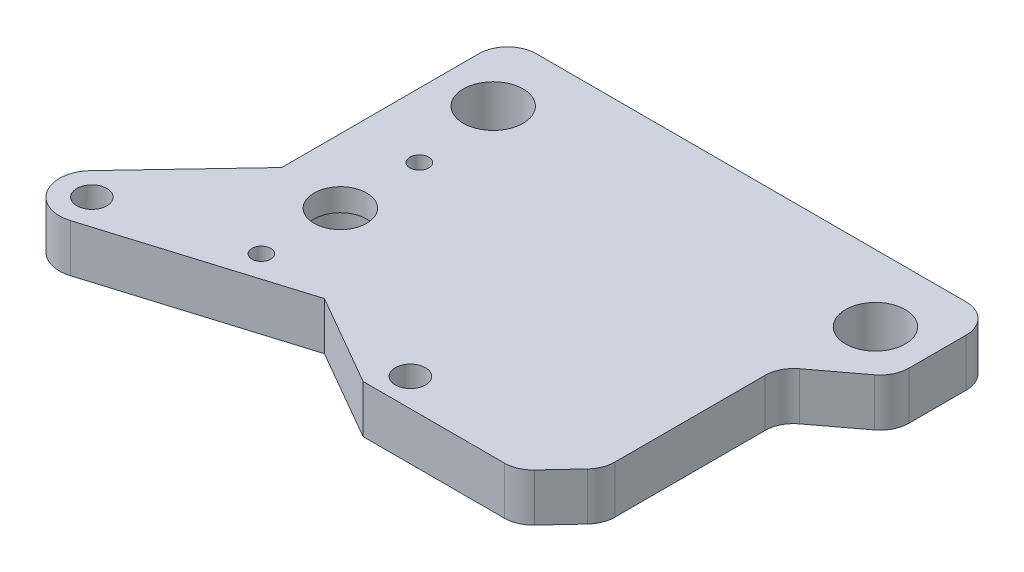
SolidWorks part; units mm, degrees
other "Markup1"
sketch "Sketch6" plane through (-23.3268, 0, -30.7975) normal (-0.0348, 0.9994, -0.0028) x (-0.9993, -0.0348, 0.0153)
sketch "Sketch7" plane through (-23.3268, 0, -30.7975) normal (-0.0348, 0.9994, -0.0028) x (-0.9993, -0.0348, 0.0153)
sketch "Sketch8" plane through (-23.3268, 0, -30.7975) normal (-0.0348, 0.9994, -0.0028) x (-0.9993, -0.0348, 0.0153)
sketch "Sketch10" plane through (-23.3268, 0, -30.7975) normal (-0.0348, 0.9994, -0.0028) x (-0.9993, -0.0348, 0.0153)
sketch "Sketch13" plane through (-23.3268, 0, -30.7975) normal (-0.0348, 0.9994, -0.0028) x (-0.9993, -0.0348, 0.0153)
sketch "Sketch15" plane through (-23.3268, 0, -30.7975) normal (-0.0348, 0.9994, -0.0028) x (-0.9993, -0.0348, 0.0153)
sketch "Sketch16" plane through (-23.3268, 0, -30.7975) normal (-0.0348, 0.9994, -0.0028) x (-0.9993, -0.0348, 0.0153)
sketch "Sketch17" plane through (-23.3268, 0, -30.7975) normal (-0.0348, 0.9994, -0.0028) x (-0.9993, -0.0348, 0.0153)
sketch "Sketch18" plane through (-23.3268, 0, -30.7975) normal (-0.0348, 0.9994, -0.0028) x (-0.9993, -0.0348, 0.0153)
sketch "Sketch19" plane through (-23.3268, 0, -30.7975) normal (-0.0348, 0.9994, -0.0028) x (-0.9993, -0.0348, 0.0153)
sketch "Sketch21" plane through (-23.3268, 0, -30.7975) normal (-0.0348, 0.9994, -0.0028) x (-0.9993, -0.0348, 0.0153)
sketch "Sketch23" plane through (-23.3268, 0, -30.7975) normal (-0.0348, 0.9994, -0.0028) x (-0.9993, -0.0348, 0.0153)
sketch "Sketch24" plane through (-23.3268, 0, -30.7975) normal (-0.0348, 0.9994, -0.0028) x (-0.9993, -0.0348, 0.0153)
sketch "Sketch25" plane through (-23.3268, 0, -30.7975) normal (-0.0348, 0.9994, -0.0028) x (-0.9993, -0.0348, 0.0153)
sketch "Sketch26" plane through (-23.3268, 0, -30.7975) normal (-0.0348, 0.9994, -0.0028) x (-0.9993, -0.0348, 0.0153)
sketch "Sketch27" plane through (-23.3268, 0, -30.7975) normal (-0.0348, 0.9994, -0.0028) x (-0.9993, -0.0348, 0.0153)
sketch "Sketch28" [suppressed] plane through (-23.3268, 0, -30.7975) normal (-0.0348, 0.9994, -0.0028) x (-0.9993, -0.0348, 0.0153)
sketch "Sketch29" plane through (-23.3268, 0, -30.7975) normal (-0.0348, 0.9994, -0.0028) x (-0.9993, -0.0348, 0.0153)
sketch "Sketch30" plane through (-23.3268, 0, -30.7975) normal (-0.0348, 0.9994, -0.0028) x (-0.9993, -0.0348, 0.0153)
sketch "Sketch32" plane through (-23.3268, 0, -30.7975) normal (-0.0348, 0.9994, -0.0028) x (-0.9993, -0.0348, 0.0153)
material "6061-T6 (SS)"
ref_plane "X-Y Datum" through (0, 0, 0) normal (0, 0, 1) x (1, 0, 0)
ref_plane "X-Z Datum" through (0, 0, 0) normal (0, 1, 0) x (1, 0, 0)
ref_plane "Y-Z Datum" through (0, 0, 0) normal (1, 0, 0) x (0, 0, -1)
other "Graphic1"
other "Graphic (Closed) -1"
other "Graphic (Closed) -2"
sketch "Sketch2" plane through (0, 0, 0) normal (0, 1, 0) x (1, 0, 0)
  line L0 (48.6426, -18.7325) -> (-23.0162, -18.7325)
  line L1 (24.0125, -14.7036) -> (25.7865, -13.7801) construction
  line L2 (0, 0) -> (105.5557, -202.7707) construction
  line L3 (11.142, -21.4036) -> (-3.5026, -29.027) construction
  line L4 (0, 0) -> (0, -121.3797) construction
  line L5 (-3.5026, -29.027) -> (90.9112, -210.3941) construction
  line L6 (90.9112, -210.3941) -> (105.5557, -202.7707) construction
  line L7 (11.142, -21.4036) -> (24.0125, -14.7036) construction
  line L11 (-12.7, 30.7975) -> (57.15, 30.7975)
  line L12 (57.15, 13.0175) -> (57.15, 30.7975)
  line L13 (57.15, 13.0175) -> (-12.7, 13.0175) construction
  line L15 (44.7685, -18.0975) -> (44.7685, -11.3157) construction
  line L16 (44.7685, -18.0975) -> (34.8625, -18.0975) construction
  line L18 (44.7685, 9.8425) -> (34.8625, 9.8425) construction
  line L20 (44.7685, -11.3157) -> (49.8485, -11.3157) construction
  line L21 (49.8485, -11.3157) -> (49.8485, 3.0607) construction
  line L22 (49.8485, 3.0607) -> (44.7685, 3.0607) construction
  line L23 (44.7685, 3.0607) -> (44.7685, 9.8425) construction
  line L24 (34.8625, -18.0975) -> (34.8625, 9.8425) construction
  line L25 (48.6426, -18.7325) -> (57.15, 13.0175)
  line L26 (-12.7, 30.7975) -> (-12.7, 13.0175)
  line L28 (-12.5603, 0) -> (-16.51, -40.5272) construction
  line L30 (-23.0162, -18.7325) -> (-12.7, 13.0175)
  circle A0 centre (0, 0) radius 3.175
  circle A1 centre (24.0125, -14.7036) radius 2
  circle A2 centre (-1.5875, 21.9075) radius 3.9688
  circle A3 centre (49.2125, 21.9075) radius 3.9687
  circle A4 centre (39.8485, -4.1275) radius 5.1
  circle A5 centre (24.0125, -14.7036) radius 3.175 construction
  circle A6 centre (39.8485, -14.6275) radius 1.6
  circle A7 centre (39.8485, 6.3725) radius 1.6
  circle A8 centre (-17.2047, -14.9225) radius 3.175 construction
  circle A9 centre (-17.2047, -14.9225) radius 2
  point P9 (11.142, -21.4036)
  point P30 (49.8485, -4.1275)
  point P31 (34.8625, -4.1275)
  dimension "D1" = 6.35
  dimension "D8" = 4
  dimension "D10" = 7.9375
  dimension "D11" = 7.9375
  dimension "D16" = 27.94
  dimension "D23" = 10.2
  dimension "D20" = 6.35
  dimension "D30" = 3.2
  dimension "D32" = 3.2
  dimension "D34" = 6.35
  dimension "D35" = 4
  dimension "D3" = 13.0175
  dimension "D4" = 16.51
  dimension "D5" = 228.6
  dimension "D6" = 24.13
  dimension "D7" = 27.5
  dimension "D9" = 16.51
  dimension "D12" = 8.89
  dimension "D13" = 69.85
  dimension "D14" = 7.9375
  dimension "D15" = 31.75
  dimension "D17" = 17.78
  dimension "D18" = 3.175
  dimension "D19" = 14.986
  dimension "D21" = 5.08
  dimension "D22" = 14.3764
  dimension "D24" = 10
  dimension "D25" = 36.83
  dimension "D26" = 50.8
  dimension "D27" = 165
  dimension "D28" = 12.7
  dimension "D29" = 17.3015
  dimension "D31" = 10.5
  dimension "D33" = 10.5
  dimension "D36" = 162
extrude "Boss-Extrude1" [suppressed] add sketch "Sketch2" against normal blind 6.35
ref_point "Point1" [suppressed]
sketch "Sketch3" [suppressed] plane through (0, 0, 0) normal (0, 1, 0) x (1, 0, 0)
  line L0 (39.9681, 6.3725) -> (39.9681, -4.1275) construction
  line L1 (57.2697, 12.9663) -> (-12.5803, 12.9663) construction
  line L5 (39.9681, -4.1275) -> (39.9681, -14.6275) construction
  line L6 (42.0297, -18.7325) -> (20.4164, -18.7325)
  line L7 (57.2697, 12.9663) -> (57.2697, 30.7975)
  line L8 (57.2697, 30.7975) -> (-12.5803, 30.7975)
  line L9 (-12.5803, 30.7975) -> (-12.5803, 12.9663)
  line L10 (40.938, 24.6176) -> (16.9472, 10.7666)
  line L11 (13.3942, 11.8528) -> (6.9035, 25.1608)
  line L12 (8.045, 26.9875) -> (40.303, 26.9875)
  line L13 (57.2697, 12.9663) -> (48.3797, 12.9663)
  line L14 (48.3797, 12.9663) -> (48.3797, -12.3825)
  line L16 (-23.0162, -18.7325) -> (48.6426, -18.7325) construction
  line L18 (16.6064, -14.8627) -> (10.2787, -14.8627)
  line L21 (-8.965, -15.5427) -> (-15.106, -18.7325)
  line L24 (-21.1701, -13.6017) -> (-12.5803, 12.9663)
  line L29 (17.8764, -16.1925) -> (17.8764, -16.1327)
  circle A0 centre (0.1197, 0) radius 3.175
  circle A1 centre (-1.4678, 21.9075) radius 3.9688
  circle A2 centre (49.3322, 21.9075) radius 3.9687
  circle A3 centre (39.9681, -4.1275) radius 5.1
  circle A4 centre (39.9681, -14.6275) radius 1.6
  circle A5 centre (39.9681, 6.3725) radius 1.6
  circle A6 centre (24.1322, -14.7036) radius 2
  circle A7 centre (-17.085, -14.9225) radius 2
  arc A8 (13.3942, 11.8528) -> (16.9472, 10.7666) centre (15.6772, 12.9663) ccw
  arc A9 (8.045, 26.9875) -> (6.9035, 25.1608) centre (8.045, 25.7175) ccw
  arc A10 (40.938, 24.6176) -> (40.303, 26.9875) centre (40.303, 25.7175) ccw
  arc A11 (10.2787, -14.8627) -> (-8.965, -15.5427) centre (0.1197, 0) cw
  arc A12 (-15.106, -18.7325) -> (-21.1701, -13.6017) centre (-17.085, -14.9225) cw
  arc A13 (42.0297, -18.7325) -> (48.3797, -12.3825) centre (42.0297, -12.3825) ccw
  arc A14 (20.4164, -18.7325) -> (17.8764, -16.1925) centre (20.4164, -16.1925) cw
  arc A15 (16.6064, -14.8627) -> (17.8764, -16.1327) centre (16.6064, -16.1327) cw
  dimension "D1" = 6.35
  dimension "D4" = 7.9375
  dimension "D9" = 10.2
  dimension "D10" = 3.2
  dimension "D11" = 4
  dimension "D21" = 2.54
  dimension "D22" = 1.27
  dimension "D3" = 6.35
  dimension "D28" = 2.54
  dimension "D29" = 1.27
  dimension "D2" = 7.9375
  dimension "D5" = 50.8
  dimension "D6" = 21.9075
  dimension "D7" = 1.5875
  dimension "D8" = 8.89
  dimension "D12" = 10.5
  dimension "D13" = 17.2047
  dimension "D14" = 24.0125
  dimension "D15" = 14.7036
  dimension "D16" = 39.8485
  dimension "D17" = 4.1275
  dimension "D18" = 14.9225
  dimension "D19" = 69.85
  dimension "D20" = 3.81
  dimension "D23" = 30
  dimension "D24" = 64
  dimension "D25" = 32.258
  dimension "D26" = 15.5575
  dimension "D27" = 25.3488
  dimension "D30" = 8.89
sketch "Sketch4" plane through (0, 0, 0) normal (0, 1, 0) x (1, 0, 0)
  line L0 (39.8485, 6.3725) -> (39.8485, -4.1275) construction
  line L1 (56.1975, 13.0175) -> (-8.5725, 13.0175) construction
  line L2 (39.8485, -4.1275) -> (39.8485, -14.6275) construction
  line L3 (40.2577, -18.4375) -> (21.466, -18.4375)
  line L5 (52.3875, 30.7975) -> (-4.7625, 30.7975)
  line L6 (-8.5725, 26.9875) -> (-8.5725, 0.7817)
  line L40 (47.4685, 8.9851) -> (47.4685, -10.9806)
  line L41 (46.4449, -13.579) -> (43.0442, -17.2259)
  line L43 (48.9856, 12.0279) -> (54.6804, 16.3193)
  line L44 (56.1975, 19.3621) -> (56.1975, 26.9875)
  line L48 (-8.5725, 0.7817) -> (-20.9174, -12.2732)
  line L50 (-17.78, -15.24) -> (0, 0) construction
  line L58 (21.466, -18.4375) -> (9.3466, -11.4637)
  line L59 (0, 0) -> (0, 5.6144) construction
  line L60 (9.3466, -11.4637) -> (-16.5178, -19.3694)
  circle A0 centre (0, 0) radius 5
  circle A1 centre (-1.5875, 21.9075) radius 3.9688
  circle A2 centre (49.2125, 21.9075) radius 3.9687
  circle A6 centre (24.0125, -14.7036) radius 2
  circle A7 centre (-17.78, -15.24) radius 2
  arc A12 (-15.328, -18.7942) -> (-20.9174, -12.2732) centre (-17.78, -15.24) cw
  arc A19 (-8.5725, 26.9875) -> (-4.7625, 30.7975) centre (-4.7625, 26.9875) cw
  arc A20 (52.3875, 30.7975) -> (56.1975, 26.9875) centre (52.3875, 26.9875) cw
  circle A33 centre (24.0125, -14.7036) radius 3.5 construction
  arc A45 (56.1975, 19.3621) -> (54.6804, 16.3193) centre (52.3875, 19.3621) cw
  arc A46 (47.4685, 8.9851) -> (48.9856, 12.0279) centre (51.2785, 8.9851) cw
  arc A47 (47.4685, -10.9806) -> (46.4449, -13.579) centre (43.6585, -10.9806) cw
  arc A48 (43.0442, -17.2259) -> (40.2577, -18.4375) centre (40.2577, -14.6275) cw
  circle A49 centre (0, -10.5) radius 1.25
  circle A50 centre (0, 10.5) radius 1.25
  point P58 (-8.5725, 30.7975)
  point P77 (56.1975, 17.4625)
  point P84 (41.9143, -18.4375)
  dimension "D1" = 10
  dimension "D2" = 7.9375
  dimension "D8" = 4
  dimension "D25" = 3.81
  dimension "D26" = 7
  dimension "D33" = 4.318
  dimension "D38" = 10.5
  dimension "D23" = 3.81
  dimension "D46" = 2.5
  dimension "D45" = 3.81
  dimension "D3" = 50.8
  dimension "D4" = 21.9075
  dimension "D5" = 1.5875
  dimension "D9" = 10.5
  dimension "D10" = 24.0125
  dimension "D11" = 14.7036
  dimension "D12" = 39.8485
  dimension "D13" = 4.1275
  dimension "D14" = 15.24
  dimension "D15" = 17.78
  dimension "D16" = 6.985
  dimension "D17" = 8.89
  dimension "D21" = 17.78
  dimension "D24" = 7.62
  dimension "D36" = 9.525
  dimension "D40" = 127
  dimension "D41" = 10.5
  dimension "D43" = 137
  dimension "D60" = 6.985
extrude "Boss-Extrude2" add sketch "Sketch4" against normal blind 6.35
ref_point "Point2"
ref_point "Point3"
ref_point "Point4"
sketch "Sketch31" [suppressed] plane through (0, -6.35, 0) normal (0, -1, 0) x (1, 0, 0)
  circle A0 centre (0, 0) radius 3.5
  circle A1 centre (0, 0) radius 5
  dimension "D1" = 7
extrude "Boss-Extrude5" [suppressed] add sketch "Sketch31" against normal blind 3
sketch "Sketch33" plane through (0, 0, 0) normal (0, 1, 0) x (1, 0, 0)
  circle A0 centre (0, 0) radius 5
  circle A1 centre (0, 0) radius 3.5
  dimension "D1" = 7
extrude "Boss-Extrude6" add sketch "Sketch33" against normal blind 3
